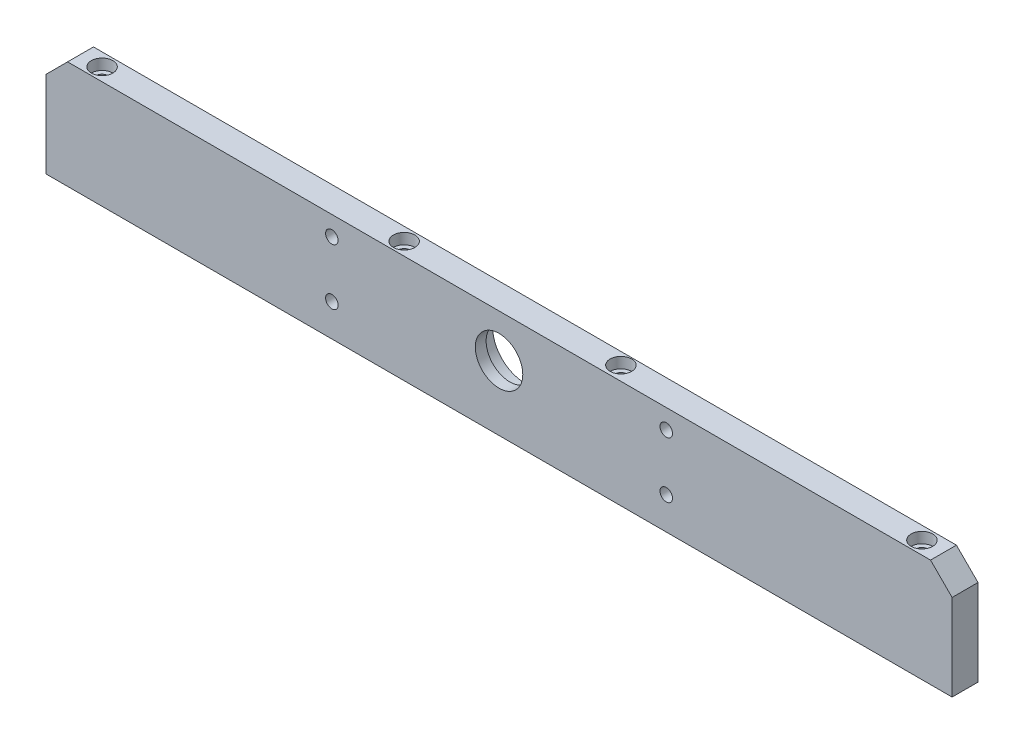
SolidWorks part; units mm, degrees
material "铝材"
ref_plane "前基準面" through (0, 0, 0) normal (0, 0, 1) x (1, 0, 0)
ref_plane "上基準面" through (0, 0, 0) normal (0, 1, 0) x (1, 0, 0)
ref_plane "右基準面" through (0, 0, 0) normal (1, 0, 0) x (0, 0, -1)
sketch "草图1" plane through (0, 0, 0) normal (0, 0, 1) x (1, 0, 0)
  line L1 (0, 0) -> (420, 0)
  line L2 (0, 0) -> (0, 50)
  line L3 (0, 50) -> (420, 50)
  line L4 (420, 0) -> (420, 50)
  dimension "D1" = 420
  dimension "D2" = 50
extrude "凸台-拉伸1" add sketch "草图1" along normal blind 12
chamfer "倒角1" distance 10 angle 45 2 edges at (420, 50, 6) (0, 50, 6)
sketch "草图2" plane through (0, 0, 12) normal (0, 0, 1) x (1, 0, 0)
  line L0 (210, 0) -> (210, 50) construction
  line L1 (0, 0) -> (420, 0) construction
  line L2 (410, 50) -> (10, 50) construction
  circle A0 centre (210, 30) radius 11
  dimension "D1" = 22
  dimension "D2" = 30
extrude "切除-拉伸1" cut sketch "草图2" against normal through all
sketch "草图3" plane through (0, 0, 0) normal (0, 0, -1) x (-1, 0, 0)
  circle A0 centre (-210, 30) radius 15
  dimension "D1" = 30
extrude "切除-拉伸2" cut sketch "草图3" against normal blind 7
hole_wizard "M5 六角凹头螺钉的柱形沉头孔1" positions "草图5" profile "草图4" counterbore size "M5" standard "ISO" end condition through all
sketch "草图5" plane through (0, 50, 0) normal (0, 1, 0) x (-1, 0, 0)
  line L0 (-10, 6) -> (-410, 6) construction
  line L1 (-10, 0) -> (-10, 12) construction
  line L2 (-410, 12) -> (-410, 0) construction
  point P0 (-20, 6)
  point P1 (-160, 6)
  point P3 (-260, 5.5285)
  point P5 (-400, 6)
  dimension "D1" = 10
  dimension "D2" = 140
  dimension "D3" = 10
  dimension "D4" = 140
sketch "草图4" plane through (20, 50, 6) normal (1, 0, 0) x (0, 0, 1)
  line L0 (0, 0) -> (0, 50)
  line L1 (0, 50) -> (2.9, 50)
  line L3 (2.9, 50) -> (2.9, 5)
  line L4 (2.9, 5) -> (5, 5)
  line L5 (5, 5) -> (5, 0)
  line L7 (5, 0) -> (0, 0)
  line L11 (0, -6.35) -> (0, 107.95) construction
  dimension "通孔孔直径" = 5.8
  dimension "通孔孔深度" = 50
  dimension "柱形沉头孔直径" = 10
  dimension "柱形沉头孔深度" = 5
hole_wizard "M5 六角凹头螺钉的柱形沉头孔2" positions "草图7" profile "草图6" counterbore size "M5" standard "ISO" end condition through all
sketch "草图7" plane through (0, 0, 0) normal (0, 0, -1) x (-1, 0, 0)
  point P1 (-287.5, 41)
  point P4 (-287.5, 15)
  point P7 (-132.5, 41)
  point P10 (-132.5, 15)
sketch "草图6" plane through (287.5, 41, 0) normal (1, 0, 0) x (0, 1, 0)
  line L0 (0, 0) -> (0, 12)
  line L1 (0, 12) -> (2.9, 12)
  line L3 (2.9, 12) -> (2.9, 5)
  line L4 (2.9, 5) -> (5, 5)
  line L5 (5, 5) -> (5, 0)
  line L7 (5, 0) -> (0, 0)
  line L11 (0, -6.35) -> (0, 107.95) construction
  dimension "通孔孔直径" = 5.8
  dimension "通孔孔深度" = 12
  dimension "柱形沉头孔直径" = 10
  dimension "柱形沉头孔深度" = 5
hole_wizard "M4 螺纹孔1" positions "草图9" profile "草图8" tap size "M4" standard "ISO"
sketch "草图9" plane through (0, 0, 0) normal (0, 0, -1) x (-1, 0, 0)
  line L0 (-410, 50) -> (-10, 50) construction
  line L1 (-420, 0) -> (-420, 40) construction
  point P0 (-243, 25.5)
  point P1 (-243, 10.5)
  dimension "D1" = 15
  dimension "D2" = 24.5
  dimension "D3" = 177
sketch "草图8" plane through (243, 25.5, 0) normal (1, 0, 0) x (0, 1, 0)
  line L0 (0, 0) -> (0, 11.0914)
  line L1 (0, 11.0914) -> (1.65, 10.1)
  line L2 (1.65, 10.1) -> (1.65, 0)
  line L5 (1.65, 0) -> (0, 0)
  line L10 (0, 11.0914) -> (-1.65, 10.1) construction
  line L11 (0, -6.35) -> (0, 107.95) construction
  dimension "螺纹孔钻头直径" = 3.3
  dimension "螺纹孔钻头深度" = 10.1
  dimension "导头角度" = 118
cosmetic thread "孔螺蚊线1" parameters "D1"=8, "D2"=4
cosmetic thread "孔螺蚊线2" parameters "D1"=8, "D2"=4
